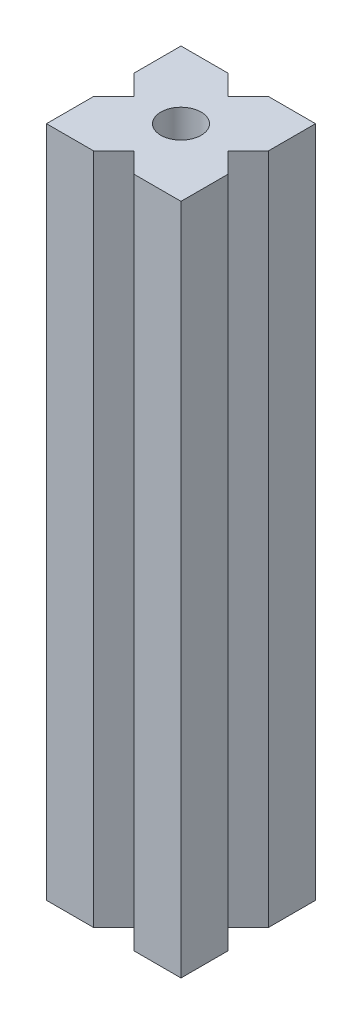
SolidWorks part; units mm, degrees
ref_plane "Front" through (0, 0, 0) normal (0, 0, 1) x (1, 0, 0)
ref_plane "Top" through (0, 0, 0) normal (0, 1, 0) x (1, 0, 0)
ref_plane "Right" through (0, 0, 0) normal (1, 0, 0) x (0, 0, -1)
sketch "Skizze1" plane through (0, 0, 0) normal (0, 1, 0) x (1, 0, 0)
  line L1 (0, 0) -> (20, 0)
  line L2 (0, 0) -> (0, 20)
  line L3 (0, 20) -> (20, 20)
  line L4 (20, 0) -> (20, 20)
  dimension "D1" = 20
extrude "Aufsatz-Linear austragen1" add sketch "Skizze1" along normal blind 100
sketch "Skizze2" plane through (0, 100, 0) normal (0, 1, 0) x (1, 0, 0)
  line L0 (10, 20) -> (10, 0) construction
  line L1 (0, 10) -> (20, 10) construction
  line L2 (7, 20) -> (10, 17)
  line L3 (13, 20) -> (10, 17)
  line L4 (10, 10) -> (20, 20) construction
  line L5 (7, 20) -> (13, 20)
  line L6 (20, 13) -> (17, 10)
  line L7 (20, 7) -> (17, 10)
  line L8 (20, 7) -> (20, 13)
  line L9 (0, 7) -> (0, 13)
  line L10 (0, 7) -> (3, 10)
  line L11 (0, 13) -> (3, 10)
  line L12 (7, 0) -> (13, 0)
  line L13 (13, 0) -> (10, 3)
  line L14 (7, 0) -> (10, 3)
  line L15 (20, 20) -> (0, 20) construction
  line L16 (20, 0) -> (20, 20) construction
  line L17 (0, 0) -> (20, 0) construction
  dimension "D1" = 3
  dimension "D2" = 3
extrude "Schnitt-Linear austragen1" cut sketch "Skizze2" against normal through all
sketch "Sketch1" plane through (0, 100, 0) normal (0, 1, 0) x (1, 0, 0)
  line L0 (10, 17) -> (10, 3) construction
  circle A0 centre (10, 10) radius 3
  dimension "D1" = 6
extrude "Extrude1" cut sketch "Sketch1" against normal through all
